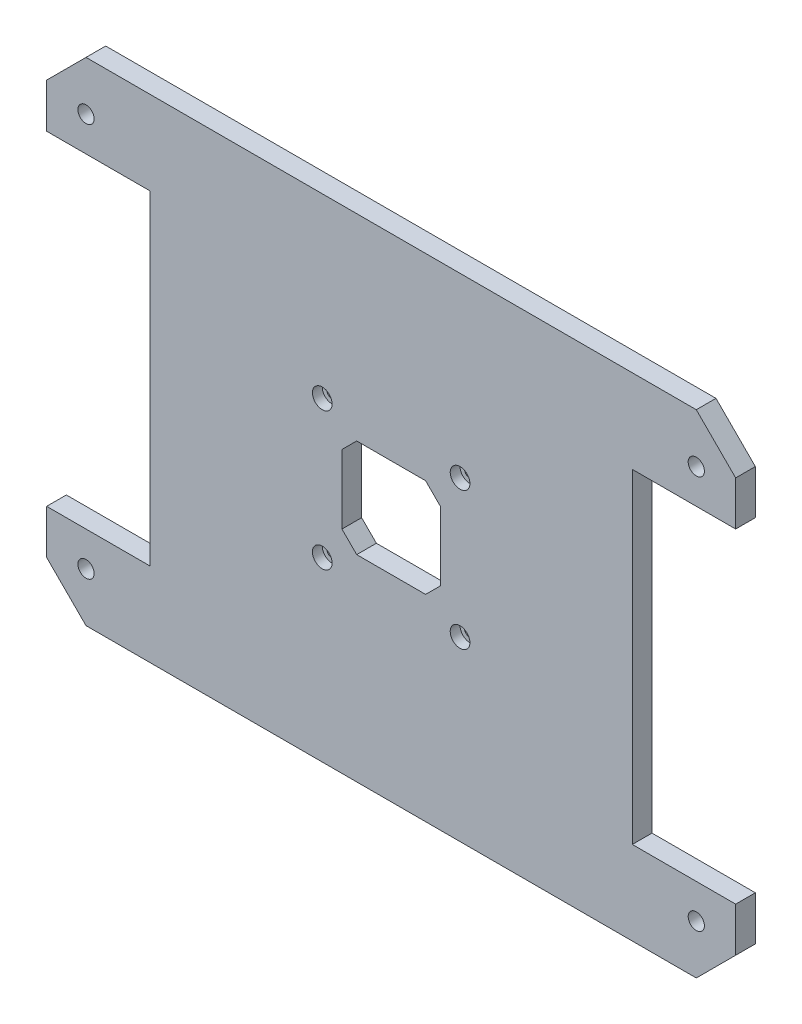
SolidWorks part; units mm, degrees
ref_plane "前视基准面" through (0, 0, 0) normal (0, 0, 1) x (1, 0, 0)
ref_plane "上视基准面" through (0, 0, 0) normal (0, 1, 0) x (1, 0, 0)
ref_plane "右视基准面" through (0, 0, 0) normal (1, 0, 0) x (0, 0, -1)
other "Configuration Table"
sketch "草图1" plane through (0, 0, 0) normal (0, 0, 1) x (1, 0, 0)
  line L0 (-62, -50) -> (62, -50)
  line L1 (62, -50) -> (70, -42)
  line L2 (70, -42) -> (70, 42)
  line L3 (70, 42) -> (62, 50)
  line L4 (62, 50) -> (-62, 50)
  line L5 (-62, 50) -> (-70, 42)
  line L6 (-70, 42) -> (-70, -42)
  line L7 (-70, -42) -> (-62, -50)
  line L8 (-7, -10) -> (7, -10)
  line L9 (7, -10) -> (10, -7)
  line L10 (10, -7) -> (10, 7)
  line L11 (10, 7) -> (7, 10)
  line L12 (7, 10) -> (-7, 10)
  line L13 (-7, 10) -> (-10, 7)
  line L14 (-10, 7) -> (-10, -7)
  line L15 (-10, -7) -> (-7, -10)
  circle A0 centre (-62, -40) radius 1.65
  circle A1 centre (-14, -14) radius 1.1
  circle A2 centre (-62, 40) radius 1.65
  circle A3 centre (-14, 14) radius 1.1
  circle A4 centre (62, -40) radius 1.65
  circle A5 centre (14, -14) radius 1.1
  circle A6 centre (62, 40) radius 1.65
  circle A7 centre (14, 14) radius 1.1
extrude "相机底部法兰_四毫米" add sketch "草图1" along normal blind 4 from offset 4
sketch "草图2" plane through (0, 0, 0) normal (0, 0, 1) x (1, 0, 0)
  line L0 (49, -33) -> (81, -33)
  line L1 (81, -33) -> (81, 33)
  line L2 (81, 33) -> (49, 33)
  line L3 (49, 33) -> (49, -33)
  line L4 (-81, -33) -> (-49, -33)
  line L5 (-49, -33) -> (-49, 33)
  line L6 (-49, 33) -> (-81, 33)
  line L7 (-81, 33) -> (-81, -33)
extrude "两侧斜脚座敞口避让" cut sketch "草图2" along normal blind 4 from offset 4
sketch "草图3" plane through (0, 0, 0) normal (0, 0, 1) x (1, 0, 0)
  circle A0 centre (-14, -14) radius 2
  circle A1 centre (-14, 14) radius 2
  circle A2 centre (14, -14) radius 2
  circle A3 centre (14, 14) radius 2
extrude "M2头部内藏沉台" cut sketch "草图3" along normal blind 2 from offset 2
